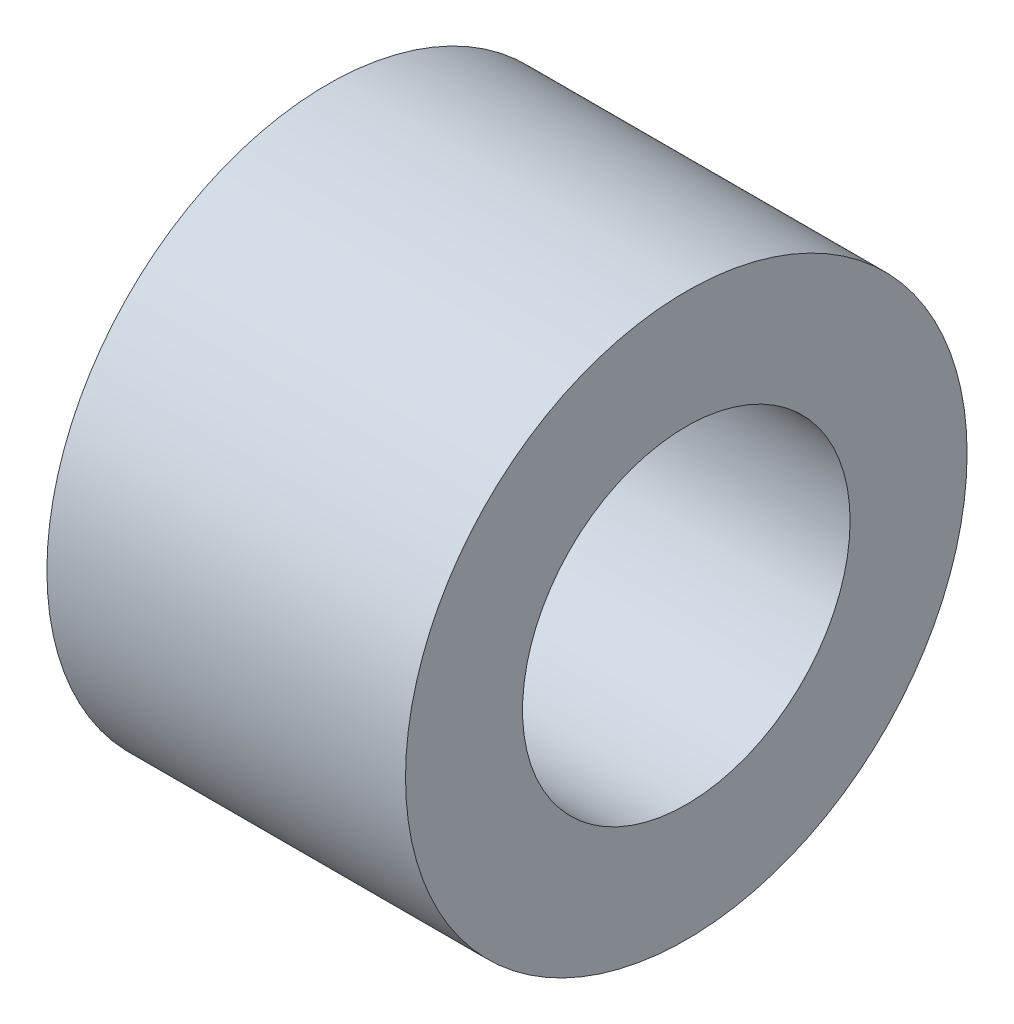
SolidWorks part; units mm, degrees
ref_plane "Front Plane" through (0, 0, 0) normal (0, 0, 1) x (1, 0, 0)
ref_plane "Top Plane" through (0, 0, 0) normal (0, 1, 0) x (1, 0, 0)
ref_plane "Right Plane" through (0, 0, 0) normal (1, 0, 0) x (0, 0, -1)
sketch "Sketch1" plane through (0, 0, 0) normal (1, 0, 0) x (0, 0, -1)
  circle A0 centre (0, 0) radius 3.5
  circle A1 centre (0, 0) radius 6
extrude "Boss-Extrude1" add sketch "Sketch1" along normal blind 7.6633
